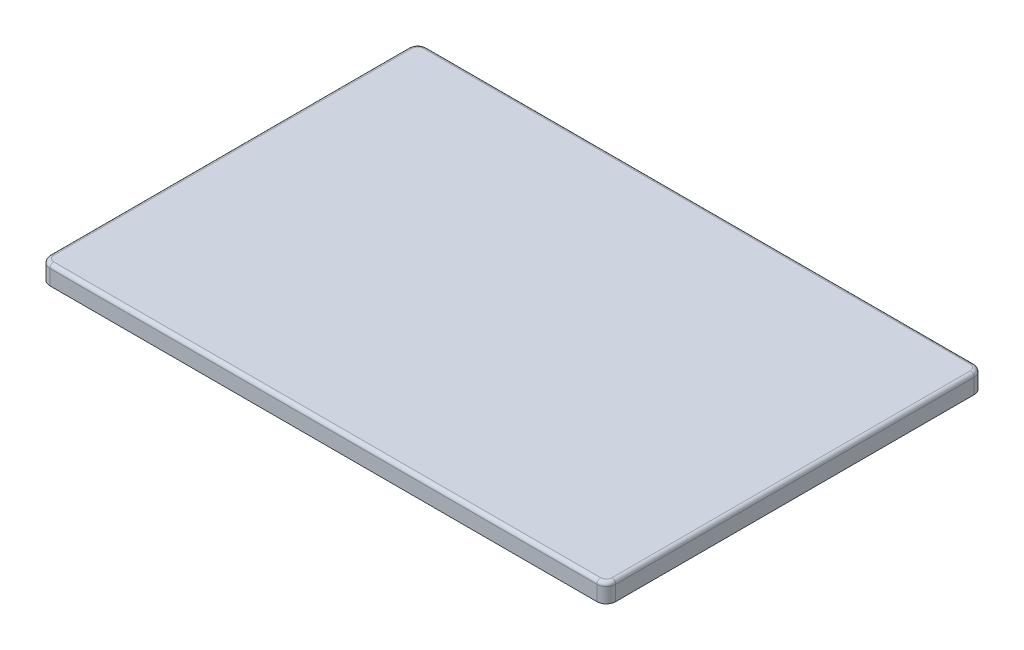
SolidWorks part; units mm, degrees
ref_plane "Front Plane" through (0, 0, 0) normal (0, 0, 1) x (1, 0, 0)
ref_plane "Top Plane" through (0, 0, 0) normal (0, 1, 0) x (1, 0, 0)
ref_plane "Right Plane" through (0, 0, 0) normal (1, 0, 0) x (0, 0, -1)
sketch "Sketch1" plane through (0, 0, 0) normal (0, 1, 0) x (1, 0, 0)
  line L1 (-145, 100) -> (145, 100)
  line L2 (-150, 95) -> (-150, -95)
  line L3 (-145, -100) -> (145, -100)
  line L4 (150, 95) -> (150, -95)
  line L5 (-150, 100) -> (150, -100) construction
  line L6 (-150, -100) -> (150, 100) construction
  arc A0 (145, 100) -> (150, 95) centre (145, 95) cw
  arc A1 (145, -100) -> (150, -95) centre (145, -95) ccw
  arc A2 (-150, -95) -> (-145, -100) centre (-145, -95) ccw
  arc A3 (-145, 100) -> (-150, 95) centre (-145, 95) ccw
  point P0 (0, 0)
  dimension "D3" = 5
  dimension "D1" = 200
  dimension "D2" = 300
extrude "Boss-Extrude1" add sketch "Sketch1" along normal blind 10
shell "Shell1" thickness 3
fillet "Fillet1" radius 2 8 edges at (148.5355, 10, 98.5355) (150, 10, 0) (148.5355, 10, -98.5355) (0, 10, -100) (-148.5355, 10, -98.5355) (-150, 10, 0) (-148.5355, 10, 98.5355) (0, 10, 100)
